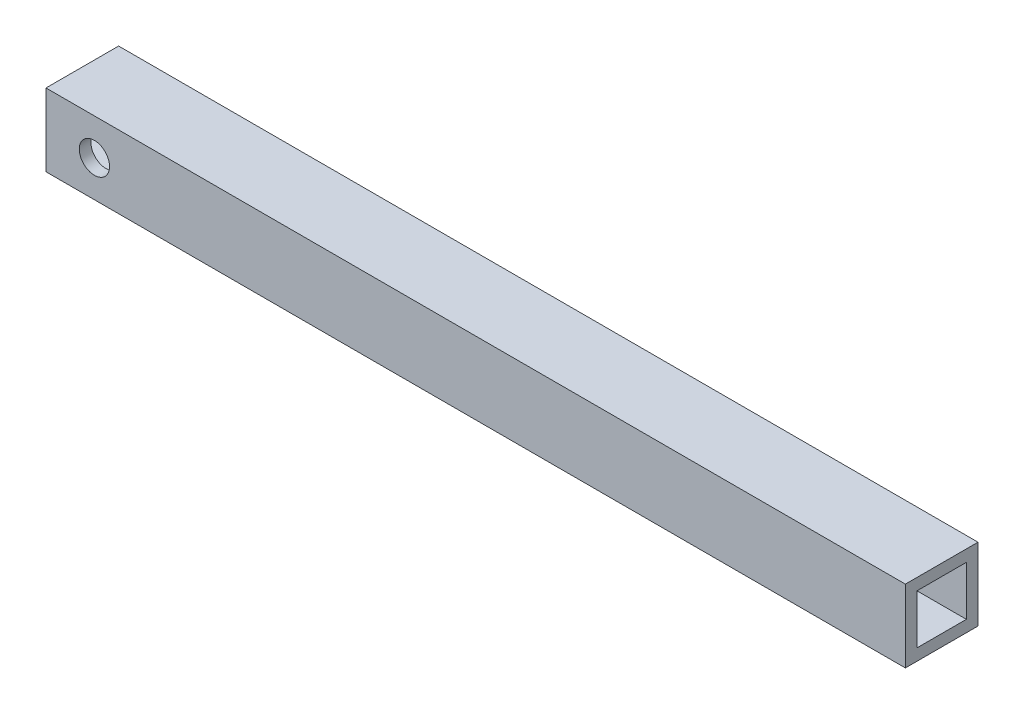
SolidWorks part; units mm, degrees
material "AISI 4340 Steel, normalized"
ref_plane "Front Plane" through (0, 0, 0) normal (0, 0, 1) x (1, 0, 0)
ref_plane "Top Plane" through (0, 0, 0) normal (0, 1, 0) x (1, 0, 0)
ref_plane "Right Plane" through (0, 0, 0) normal (1, 0, 0) x (0, 0, -1)
sketch "Sketch1" plane through (0, 0, 0) normal (1, 0, 0) x (0, 0, -1)
  line L1 (-9.525, 9.525) -> (9.525, 9.525)
  line L2 (-9.525, 9.525) -> (-9.525, -9.525)
  line L3 (-9.525, -9.525) -> (9.525, -9.525)
  line L4 (9.525, 9.525) -> (9.525, -9.525)
  line L5 (-9.525, 9.525) -> (9.525, -9.525) construction
  line L6 (-9.525, -9.525) -> (9.525, 9.525) construction
  point P0 (0, 0)
  dimension "D1" = 19.05
extrude "Boss-Extrude1" add sketch "Sketch1" along normal mid plane 225.425
shell "Shell1" thickness 3.048
sketch "Sketch3" plane through (0, 0, 9.525) normal (0, 0, 1) x (1, 0, 0)
  line L0 (112.7125, -9.525) -> (87.3125, -9.525) construction
  line L1 (112.7125, -9.525) -> (-112.7125, -9.525) construction
  line L2 (87.3125, -9.525) -> (87.3125, 9.525) construction
  line L3 (112.7125, 9.525) -> (-112.7125, 9.525) construction
  circle A0 centre (100.0125, 0) radius 3.2639
  point P10 (87.3125, 0)
  point P11 (100.0125, -9.525)
  dimension "D2" = 6.5278
  dimension "D1" = 25.4
sketch "Sketch8" plane through (0, 0, -9.525) normal (0, 0, -1) x (-1, 0, 0)
  circle A0 centre (100.0125, 0) radius 3.9688
  point P4 (0, 0)
  dimension "D3" = 7.9375
  dimension "D1" = 12.7
  dimension "D2" = 9.525
extrude "Cut-Extrude2" cut sketch "Sketch8" against normal up to surface (19.05 mm away) up to face at (0, 0, 9.525)
